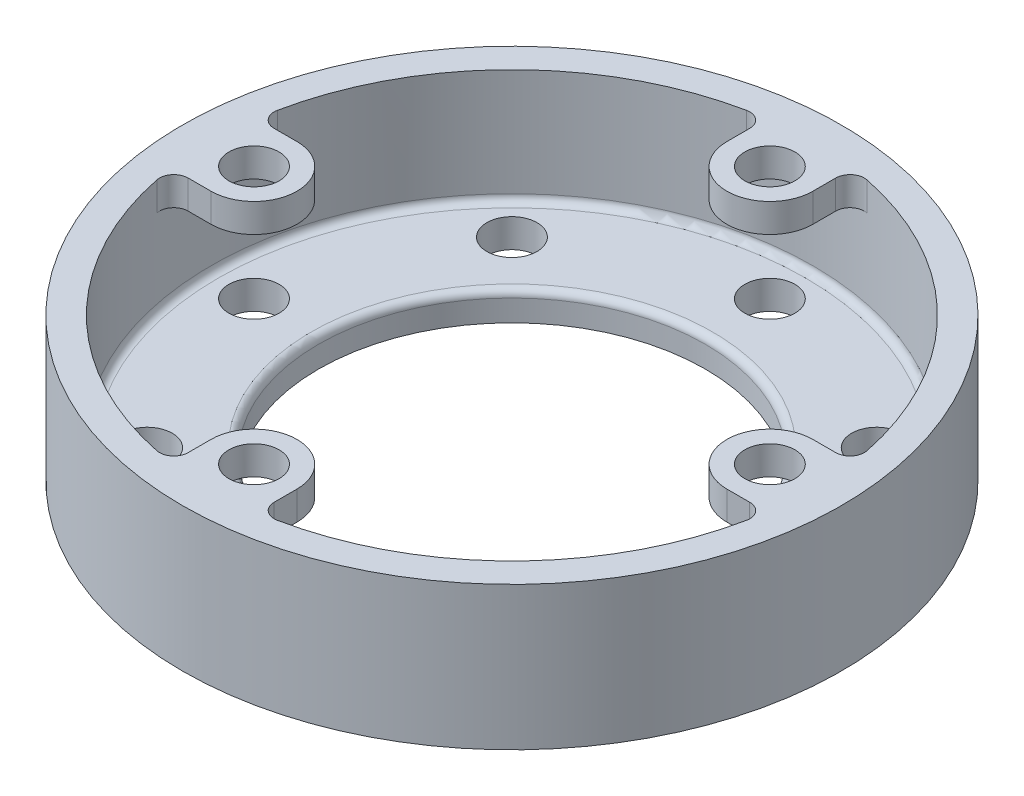
SolidWorks part; units mm, degrees
material "PW20:29:Sc:0:"
ref_plane "Front" through (0, 0, 0) normal (0, 0, 1) x (1, 0, 0)
ref_plane "Top" through (0, 0, 0) normal (0, 1, 0) x (1, 0, 0)
ref_plane "Right" through (0, 0, 0) normal (1, 0, 0) x (0, 0, -1)
sketch "Sketch1" plane through (0, 0, 0) normal (0, 1, 0) x (1, 0, 0)
  circle A0 centre (0, 0) radius 73.025
  dimension "D2" = 146.05
extrude "Base-Extrude" add sketch "Sketch1" along normal blind 31.75
shell "Shell1" thickness 6.35
sketch "Sketch4" plane through (0, 6.35, 0) normal (0, 1, 0) x (-1, 0, 0)
  circle A0 centre (0, 0) radius 42.8625
  dimension "D1" = 85.725
extrude "Cut-Extrude2" cut sketch "Sketch4" against normal through all
sketch "Sketch2" plane through (0, 31.75, 0) normal (0, 1, 0) x (-1, 0, 0)
  line L0 (0, -73.025) -> (0, 73.025) construction
  line L1 (-9.525, -65.9911) -> (-9.525, -57.15)
  line L2 (9.525, -57.15) -> (9.525, -65.9911)
  circle A0 centre (0, 0) radius 73.025 construction
  arc A1 (-9.525, -65.9911) -> (9.525, -65.9911) centre (0, 0) ccw
  circle A2 centre (0, 0) radius 66.675 construction
  arc A3 (-9.525, -57.15) -> (9.525, -57.15) centre (0, -57.15) cw
  point P16 (1.4172, 1.3651)
  dimension "D2" = 9.525
  dimension "D1" = 57.15
extrude "Boss-Extrude1" add sketch "Sketch2" against normal blind 6.35
sketch "Sketch3" plane through (0, 31.75, 0) normal (0, 1, 0) x (-1, 0, 0)
  circle A0 centre (0, -57.15) radius 5.5563
  arc A2 (9.525, -57.15) -> (-9.525, -57.15) centre (0, -57.15) ccw construction
  dimension "D1" = 11.1125
extrude "Cut-Extrude1" cut sketch "Sketch3" against normal up to next
fillet "Fillet1" radius 3.175 2 edges at (-9.525, 28.575, -65.9911) (9.525, 28.575, -65.9911)
pattern_circular "CirPattern1" count 4 every 90 about axis through (0, 0, 0) along (0, 1, 0) of "Fillet1", "Boss-Extrude1", "Cut-Extrude1"
sketch "Sketch5" plane through (0, 6.35, 0) normal (0, 1, 0) x (-1, 0, 0)
  circle A0 centre (0, -57.15) radius 5.5563 construction
  circle A1 centre (0, -57.15) radius 5.5562
extrude "Cut-Extrude3" cut sketch "Sketch5" against normal through all
pattern_circular "CirPattern2" count 8 every 45 about axis through (0, 0, 0) along (0, 1, 0) of "Cut-Extrude3"
fillet "Fillet2" radius 1.5875 2 edges at (0, 6.35, 42.8625) (0, 6.35, 66.675)
